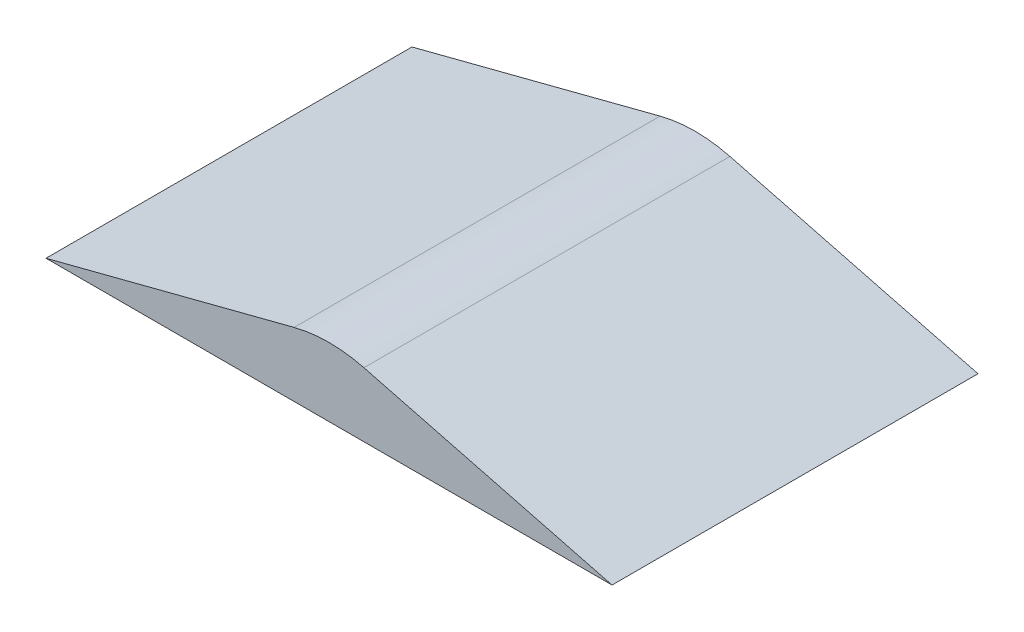
SolidWorks part; units mm, degrees
ref_plane "Front Plane" through (0, 0, 0) normal (0, 0, 1) x (1, 0, 0)
ref_plane "Top Plane" through (0, 0, 0) normal (0, 1, 0) x (1, 0, 0)
ref_plane "Right Plane" through (0, 0, 0) normal (1, 0, 0) x (0, 0, -1)
sketch "Sketch1" plane through (0, 0, 0) normal (0, 0, 1) x (1, 0, 0)
  line L0 (-151.2567, -7.6919) -> (-15.6671, 27.3739)
  line L1 (22.4908, 27.3739) -> (158.0804, -7.6919)
  line L2 (-151.2567, -7.6919) -> (158.0804, -7.6919)
  arc A0 (22.4908, 27.3739) -> (-15.6671, 27.3739) centre (3.4118, -46.3989) ccw
  point P5 (3.4118, -7.6919)
  point P6 (3.4118, 32.3081)
  dimension "D2" = 76.2
  dimension "D1" = 151
  dimension "D3" = 40
extrude "Boss-Extrude1" add sketch "Sketch1" along normal blind 200
shell "Shell1" thickness 17
sketch "Sketch3" plane through (0, 0, 0) normal (0, 1, 0) x (1, 0, 0)
  line L2 (39.37, -70.79) -> (39.37, -129.21) construction
  line L3 (-151.2567, 0) -> (158.0804, 0) construction
  line L4 (39.37, -70.79) -> (-39.37, -70.79) construction
  circle A0 centre (39.37, -70.79) radius 2.5
  circle A1 centre (-39.37, -70.79) radius 2.5
  circle A2 centre (39.37, -129.21) radius 2.5
  circle A3 centre (-39.37, -129.21) radius 2.5
  point P10 (39.37, -100)
  point P13 (0, -70.79)
  dimension "D4" = 5
  dimension "D1" = 78.74
  dimension "D2" = 58.42
  dimension "D3" = 100
